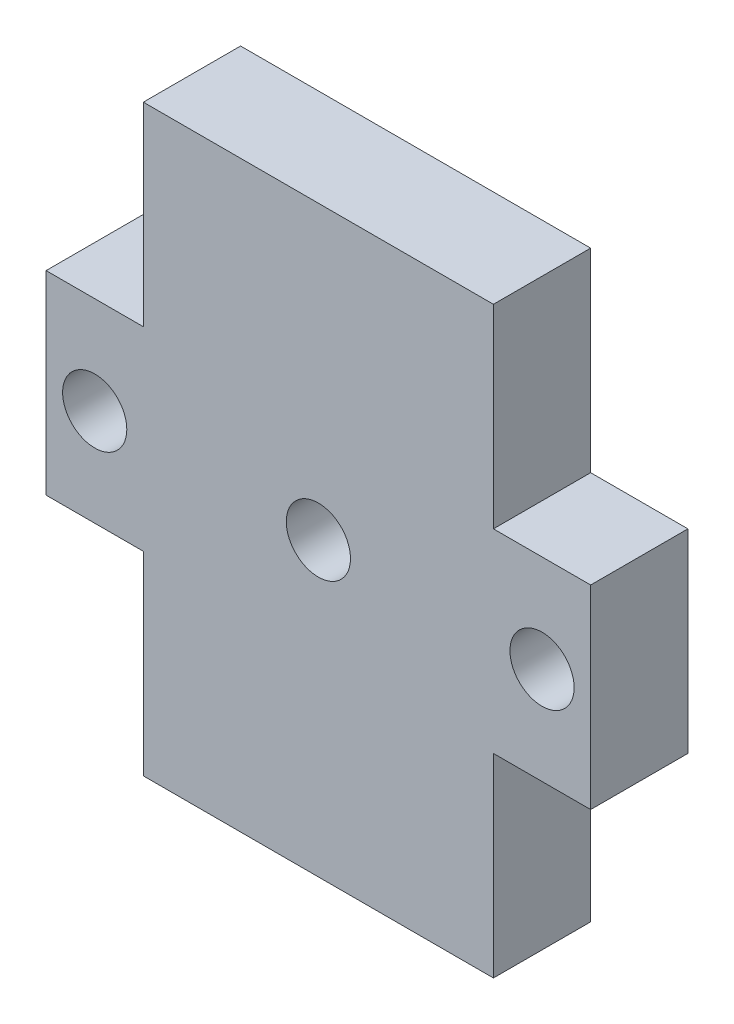
SolidWorks part; units mm, degrees
ref_plane "Front Plane" through (0, 0, 0) normal (0, 0, 1) x (1, 0, 0)
ref_plane "Top Plane" through (0, 0, 0) normal (0, 1, 0) x (1, 0, 0)
ref_plane "Right Plane" through (0, 0, 0) normal (1, 0, 0) x (0, 0, -1)
sketch "Sketch1" plane through (0, 0, 0) normal (0, 0, 1) x (1, 0, 0)
  line L1 (17.78, -19.05) -> (-17.78, -19.05)
  line L2 (17.78, -19.05) -> (17.78, 19.05)
  line L3 (17.78, 19.05) -> (-17.78, 19.05)
  line L4 (-17.78, -19.05) -> (-17.78, 19.05)
  line L5 (17.78, -19.05) -> (-17.78, 19.05) construction
  line L6 (17.78, 19.05) -> (-17.78, -19.05) construction
  point P0 (0, 0)
  dimension "D1" = 35.56
  dimension "D2" = 38.1
extrude "Boss-Extrude1" add sketch "Sketch1" along normal blind 6.35
sketch "Sketch2" plane through (0, 0, 6.35) normal (0, 0, 1) x (1, 0, 0)
  line L1 (17.78, -19.05) -> (11.43, -19.05)
  line L2 (17.78, -19.05) -> (17.78, -6.35)
  line L3 (17.78, -6.35) -> (11.43, -6.35)
  line L4 (11.43, -19.05) -> (11.43, -6.35)
  line L5 (17.78, 19.05) -> (11.43, 19.05)
  line L6 (17.78, 19.05) -> (17.78, 6.35)
  line L7 (17.78, 6.35) -> (11.43, 6.35)
  line L8 (11.43, 19.05) -> (11.43, 6.35)
  line L9 (-17.78, 19.05) -> (-11.43, 19.05)
  line L10 (-17.78, 19.05) -> (-17.78, 6.35)
  line L11 (-17.78, 6.35) -> (-11.43, 6.35)
  line L12 (-11.43, 19.05) -> (-11.43, 6.35)
  line L13 (-17.78, -19.05) -> (-11.43, -19.05)
  line L14 (-17.78, -19.05) -> (-17.78, -6.35)
  line L15 (-17.78, -6.35) -> (-11.43, -6.35)
  line L16 (-11.43, -19.05) -> (-11.43, -6.35)
  dimension "D1" = 12.7
  dimension "D2" = 6.35
extrude "Cut-Extrude1" cut sketch "Sketch2" against normal through all
sketch "Sketch3" plane through (0, 0, 6.35) normal (0, 0, 1) x (1, 0, 0)
  line L0 (11.43, -6.35) -> (17.78, 6.35) construction
  line L1 (-17.78, -6.35) -> (-11.43, 6.35) construction
  line L2 (11.43, 6.35) -> (17.78, -6.35) construction
  line L3 (-17.78, 6.35) -> (-11.43, -6.35) construction
  circle A0 centre (14.605, 0) radius 2.0955
  circle A1 centre (-14.605, 0) radius 2.0955
  dimension "D1" = 4.191
extrude "Cut-Extrude2" cut sketch "Sketch3" against normal through all
sketch "Sketch4" plane through (0, 0, 6.35) normal (0, 0, 1) x (1, 0, 0)
  circle A0 centre (0, 0) radius 2.0955
  dimension "D1" = 4.191
extrude "Cut-Extrude3" cut sketch "Sketch4" against normal through all
